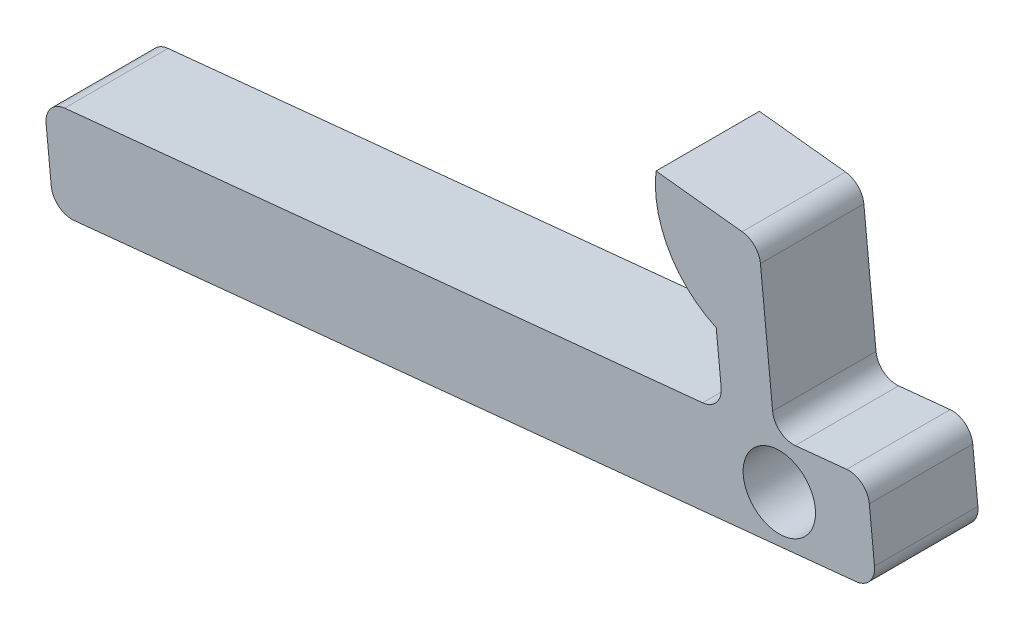
SolidWorks part; units mm, degrees
ref_plane "Front Plane" through (0, 0, 0) normal (0, 0, 1) x (1, 0, 0)
ref_plane "Top Plane" through (0, 0, 0) normal (0, 1, 0) x (1, 0, 0)
ref_plane "Right Plane" through (0, 0, 0) normal (1, 0, 0) x (0, 0, -1)
sketch "Sketch1" plane through (0, 0, 0) normal (0, 0, 1) x (1, 0, 0)
  line L0 (57.7411, 36.5621) -> (56.2047, 51.9259)
  line L1 (56.2047, 51.9259) -> (46.2647, 53.0201)
  line L2 (-12.9066, 29.4973) -> (52.7659, 36.0646)
  line L4 (-12.011, 20.542) -> (58.6366, 27.6068)
  line L6 (52.7659, 36.0646) -> (52.0912, 42.8111)
  line L7 (-12.9066, 29.4973) -> (-12.011, 20.542)
  line L9 (66.6964, 37.4576) -> (67.5919, 28.5023)
  line L10 (57.7411, 36.5621) -> (66.6964, 37.4576)
  line L11 (58.6366, 27.6068) -> (67.5919, 28.5023)
  arc A1 (46.2647, 53.0201) -> (52.0912, 42.8111) centre (56.2047, 51.9259) ccw
  circle A3 centre (58.1888, 32.0844) radius 3.5
  dimension "D2" = 9
  dimension "D7" = 9
  dimension "D5" = 7
  dimension "D6" = 80
  dimension "D1" = 10
  dimension "D3" = 9
  dimension "D4" = 5
  dimension "D8" = 4.5
extrude "Boss-Extrude1" add sketch "Sketch1" along normal blind 10
fillet "Fillet1" radius 2 5 edges at (52.7659, 36.0646, 5) (67.5919, 28.5023, 5) (66.6964, 37.4576, 5) (57.7411, 36.5621, 5) (56.2047, 51.9259, 5)
ref_plane "Plane1" through (0, 0, 5) normal (0, 0, 1) x (1, 0, 0)
sketch "Sketch3" plane through (0, 0, 5) normal (0, 0, 1) x (1, 0, 0)
  line L0 (15.449, 23.288) -> (15.449, 23.551)
  line L1 (-12.011, 20.542) -> (65.6019, 28.3033) construction
  line L2 (-12.011, 20.542) -> (-12.011, 29.5869) construction
  line L3 (50.7758, 35.8656) -> (-12.9066, 29.4973) construction
  dimension "D1" = 27.46
sketch "Sketch4" plane through (0, 0, 0) normal (0, 1, 0) x (1, 0, 0)
  circle A0 centre (4.2951, -5) radius 4.5
  circle A1 centre (4.2951, -5) radius 4.5 construction
  dimension "D1" = 9
extrude "Cut-Extrude1" cut sketch "Sketch4" along normal blind 26
fillet "Fillet2" radius 2 2 edges at (-12.011, 20.542, 5) (-12.9066, 29.4973, 5)
